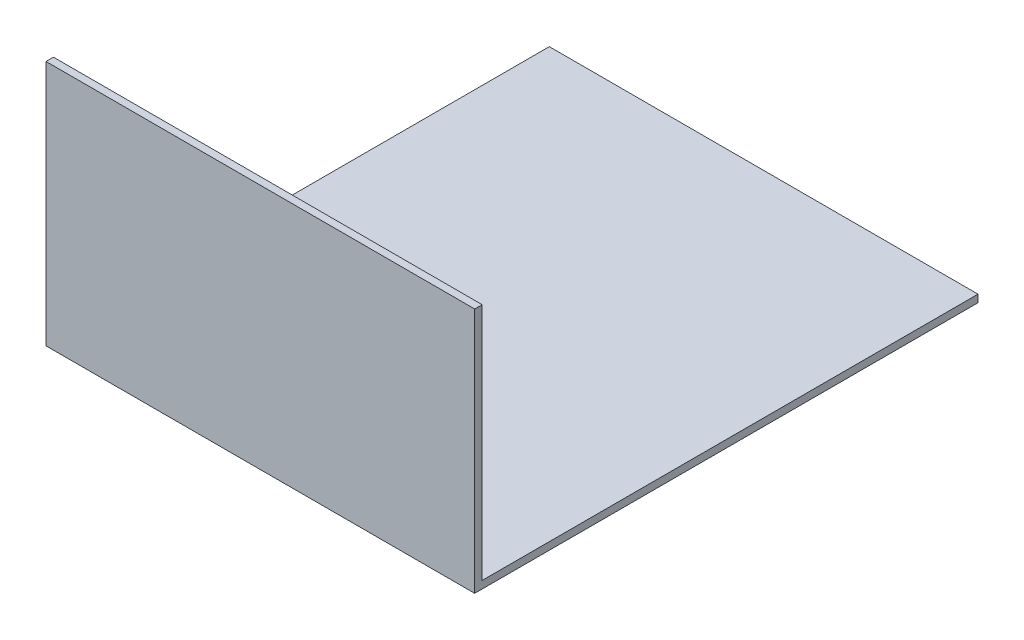
SolidWorks part; units mm, degrees
material "ABS PC"
ref_plane "Front Plane" through (0, 0, 0) normal (0, 0, 1) x (1, 0, 0)
ref_plane "Top Plane" through (0, 0, 0) normal (0, 1, 0) x (1, 0, 0)
ref_plane "Right Plane" through (0, 0, 0) normal (1, 0, 0) x (0, 0, -1)
sketch "Sketch1" plane through (0, 0, 0) normal (0, 1, 0) x (1, 0, 0)
  line L1 (-143.6, -168.6) -> (143.6, -168.6)
  line L2 (-143.6, -168.6) -> (-143.6, 168.6)
  line L3 (-143.6, 168.6) -> (143.6, 168.6)
  line L4 (143.6, -168.6) -> (143.6, 168.6)
  line L5 (-143.6, -168.6) -> (143.6, 168.6) construction
  line L6 (-143.6, 168.6) -> (143.6, -168.6) construction
  point P0 (0, 0)
  dimension "D1" = 287.2
  dimension "D2" = 337.2
extrude "Boss-Extrude1" add sketch "Sketch1" along normal blind 5
sketch "Sketch2" plane through (0, 5, 0) normal (0, 1, 0) x (1, 0, 0)
  line L0 (-143.6, 168.6) -> (-143.6, -168.6) construction
  line L1 (-143.6, -163.6) -> (143.6, -163.6)
  line L2 (-143.6, -163.6) -> (-143.6, -168.6)
  line L3 (-143.6, -168.6) -> (143.6, -168.6)
  line L4 (143.6, -163.6) -> (143.6, -168.6)
  dimension "D1" = 5
extrude "Boss-Extrude2" add sketch "Sketch2" along normal blind 160
